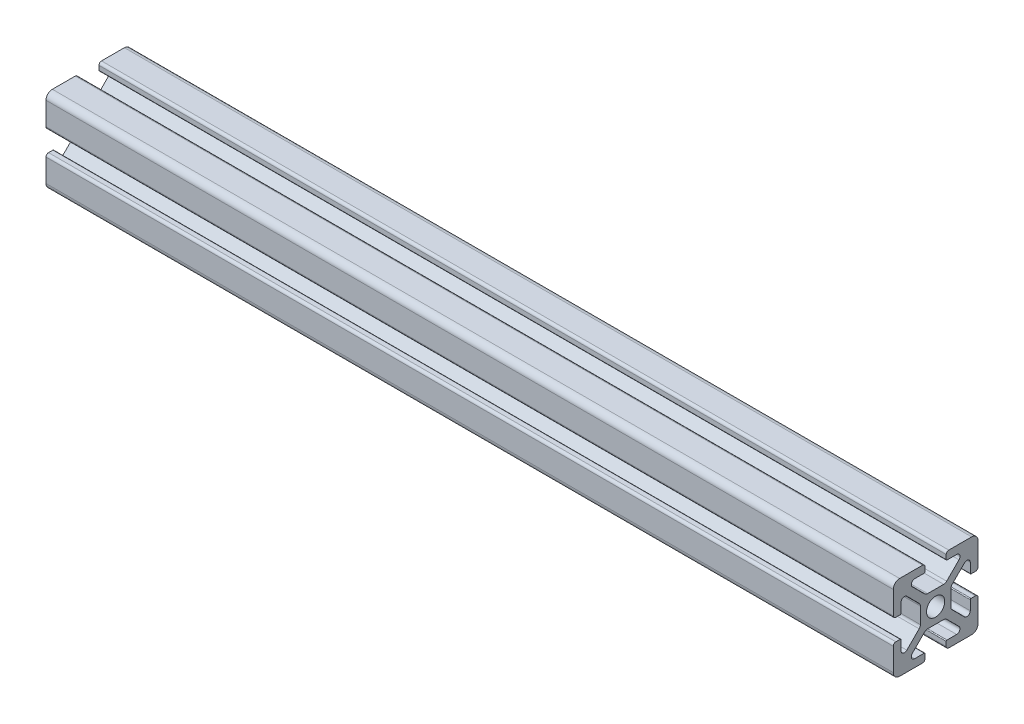
SolidWorks part; units mm, degrees
ref_plane "Front Plane" through (0, 0, 0) normal (0, 0, 1) x (1, 0, 0)
ref_plane "Top Plane" through (0, 0, 0) normal (0, 1, 0) x (1, 0, 0)
ref_plane "Right Plane" through (0, 0, 0) normal (1, 0, 0) x (0, 0, -1)
sketch "Sketch1" plane through (0, 0, 0) normal (1, 0, 0) x (0, 0, -1)
  line L0 (0, -10) -> (0, 10) construction
  line L1 (10, -10) -> (-10, -10)
  line L2 (10, -10) -> (10, 10)
  line L3 (10, 10) -> (0, 10)
  line L4 (-10, -10) -> (-10, 10)
  line L5 (10, -10) -> (-10, 10) construction
  line L6 (10, 10) -> (-10, -10) construction
  line L7 (10, 0) -> (-10, 0) construction
  line L8 (-2.5, 9.4) -> (-2.5, 8.3731)
  line L9 (-2.7, 8.1731) -> (-4.95, 8.1731)
  line L10 (-5.5157, 6.8075) -> (-2.6011, 3.8929)
  line L11 (-1.894, 3.6) -> (0, 3.6)
  line L12 (-5.3502, 4.0584) -> (-4.0584, 5.3502) construction
  line L13 (-3.825, 8.1731) -> (-3.825, 10) construction
  line L14 (-3.1, 10) -> (-10, 10)
  line L15 (-5.75, 7.3731) -> (5.75, 7.3731) construction
  circle A0 centre (0, 0) radius 2.15
  arc A1 (-4.95, 8.1731) -> (-5.5157, 6.8075) centre (-4.95, 7.3731) ccw
  arc A2 (-2.6011, 3.8929) -> (-1.894, 3.6) centre (-1.894, 4.6) ccw
  arc A3 (-2.5, 8.3731) -> (-2.7, 8.1731) centre (-2.7, 8.3731) cw
  arc A4 (-2.5, 9.4) -> (-3.1, 10) centre (-3.1, 9.4) ccw
  point P0 (0, 0)
  point P9 (0, 0)
  point P12 (0, 0)
  point P22 (-4.7043, 4.7043)
  point P32 (-2.5, 10)
  point P33 (-2.5, 8.8866)
  point P35 (-4.0584, 5.3502)
  point P37 (0, 7.3731)
  dimension "Center Hole Diameter" = 4.3
  dimension "D4" = 1
  dimension "D5" = 0.2
  dimension "D6" = 0.6
  dimension "D3" = 0.8
  dimension "Rail Height" = 20
  dimension "D7" = 6.4
  dimension "T Slot Width" = 5
  dimension "D10" = 10
  dimension "Rail Width" = 20
  dimension "D2" = 11.5
sketch "Sketch2" plane through (0, 0, 0) normal (0, 0, 1) x (1, 0, 0)
  line L0 (-80, 10) -> (-80, -10) construction
  line L1 (100, -10) -> (-100, -10) construction
  line L2 (100, -10) -> (100, 10) construction
  line L3 (100, 10) -> (-100, 10) construction
  line L4 (-100, -10) -> (-100, 10) construction
  line L5 (100, -10) -> (-100, 10) construction
  line L6 (100, 10) -> (-100, -10) construction
  line L7 (80, 10) -> (80, -10) construction
  point P0 (0, 0)
  point P12 (80, 0)
  dimension "Length" = 200
  dimension "D1" = 20
  dimension "D2" = 20
sketch "Sketch3" plane through (0, 0, 0) normal (1, 0, 0) x (0, 0, -1)
  line L0 (-5.5157, 6.8075) -> (-2.6011, 3.8929) construction
  line L5 (-3.1, 10) -> (-10, 10) construction
  line L6 (-2.5, 9.4) -> (-2.5, 8.3731) construction
  line L7 (-2.7, 8.1731) -> (-4.95, 8.1731) construction
  line L8 (-1.894, 3.6) -> (0, 3.6) construction
  line L9 (-5.5157, 6.8075) -> (-2.6011, 3.8929)
  line L10 (-10, 10) -> (0, 0) construction
  line L12 (-3.6, 1.894) -> (-3.6, 0)
  line L13 (-8.1731, 2.7) -> (-8.1731, 4.95)
  line L14 (-3.1, 10) -> (-8.5, 10)
  line L15 (-2.5, 9.4) -> (-2.5, 8.3731)
  line L16 (-2.7, 8.1731) -> (-4.95, 8.1731)
  line L17 (-1.894, 3.6) -> (0, 3.6)
  line L18 (-9.4, 2.5) -> (-8.3731, 2.5)
  line L19 (-10, 3.1) -> (-10, 8.5)
  line L20 (-6.8075, 5.5157) -> (-3.8929, 2.6011)
  line L21 (-3.6, 0) -> (-2.15, 0)
  line L22 (0, 3.6) -> (0, 2.15)
  arc A0 (-2.5, 9.4) -> (-3.1, 10) centre (-3.1, 9.4) ccw construction
  arc A1 (-2.7, 8.1731) -> (-2.5, 8.3731) centre (-2.7, 8.3731) ccw construction
  arc A2 (-4.95, 8.1731) -> (-5.5157, 6.8075) centre (-4.95, 7.3731) ccw construction
  arc A3 (-2.6011, 3.8929) -> (-1.894, 3.6) centre (-1.894, 4.6) ccw construction
  arc A4 (-2.5, 9.4) -> (-3.1, 10) centre (-3.1, 9.4) ccw
  arc A5 (-2.7, 8.1731) -> (-2.5, 8.3731) centre (-2.7, 8.3731) ccw
  arc A6 (-4.95, 8.1731) -> (-5.5157, 6.8075) centre (-4.95, 7.3731) ccw
  arc A7 (-2.6011, 3.8929) -> (-1.894, 3.6) centre (-1.894, 4.6) ccw
  arc A8 (-3.8929, 2.6011) -> (-3.6, 1.894) centre (-4.6, 1.894) cw
  arc A9 (-8.1731, 4.95) -> (-6.8075, 5.5157) centre (-7.3731, 4.95) cw
  arc A10 (-8.1731, 2.7) -> (-8.3731, 2.5) centre (-8.3731, 2.7) cw
  arc A11 (-9.4, 2.5) -> (-10, 3.1) centre (-9.4, 3.1) cw
  circle A12 centre (0, 0) radius 2.15 construction
  arc A13 (0, 2.15) -> (-2.15, 0) centre (0, 0) ccw
  arc A14 (-10, 8.5) -> (-8.5, 10) centre (-8.5, 8.5) cw
  dimension "D1" = 1.5
extrude "Boss-Extrude1" add sketch "Sketch3" against normal up to vertex (100 mm away) and the other way up to vertex (100 mm away) up to point (-100, 10, 0) other way up to point (100, 10, 0)
mirror "Mirror1" about plane through (0, 0, 0) normal (0, 1, 0) of bodies 104
mirror "Mirror2" about plane through (0, 0, 0) normal (0, 0, 1) of bodies 105
equation "\"D10@Sketch1\" = \"Rail Height@Sketch1\" / 2"
equation "\"D2@Sketch2\"=\"D1@Sketch2\""
